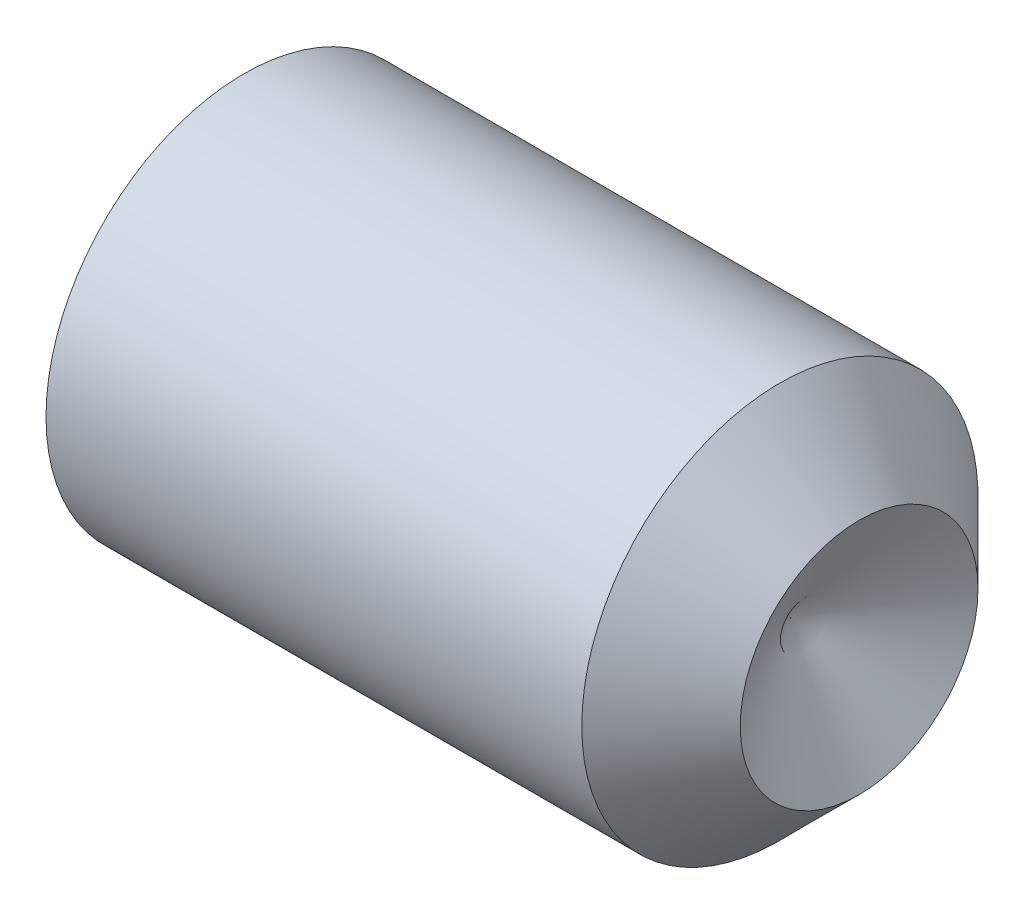
SolidWorks part; units mm, degrees
revolve "BaseBody" add sketch "BodySke" angle 360 about L5
sketch "BodySke" plane through (0, 0, 0) normal (0, 0, 1) x (1, 0, 0)
  line L0 (0, 0) -> (0, 4.172)
  line L1 (0, 4.172) -> (0.478, 5)
  line L2 (0.478, 5) -> (14, 5)
  line L3 (14, 5) -> (16, 3)
  line L4 (14.2679, 0) -> (0, 0)
  line L5 (-12.7, 0) -> (88.9, 0) construction
  line L6 (14.2679, 0) -> (16, 3)
  line L7 (16, 3) -> (16, 12.525) construction
  line L8 (0, -4.172) -> (0.478, -5) construction
  line L9 (14.2679, 0) -> (16, -3) construction
  line L10 (14, -5) -> (16, -3) construction
  line L11 (0.75, 15.875) -> (0.75, -3.175) construction
  dimension "Diameter" = 10
  dimension "Drive_ch_ang" = 60
  dimension "Minor_dia" = 8.344
  dimension "Cup_ang" = 120
  dimension "Cup_dia" = 6
  dimension "Length" = 16
  dimension "Cup_nose_ang" = 45
  dimension "Advance" = 1.5
cosmetic thread "ThreadCosmetic" [suppressed] parameters "Thread_minor"=8.344
ref_plane "Plane1" through (0, 0, 0) normal (0, 0, 1) x (1, 0, 0)
ref_plane "Plane2" through (0, 0, 0) normal (0, 1, 0) x (1, 0, 0)
ref_plane "Plane3" through (0, 0, 0) normal (1, 0, 0) x (0, 0, -1)
sketch "Sketch2" plane through (0, 0, 0) normal (-1, 0, 0) x (0, 0, 1)
  line L0 (1.4434, 2.5) -> (-1.4434, 2.5)
  line L1 (-1.4434, 2.5) -> (-2.8868, 0)
  line L2 (1.4434, 2.5) -> (2.8868, 0)
  line L3 (1.4434, -2.5) -> (2.8868, 0)
  line L4 (1.4434, -2.5) -> (-1.4434, -2.5)
  line L5 (-1.4434, -2.5) -> (-2.8868, 0)
  dimension "Hex_size" = 5
  dimension "D2" = 2.5
  dimension "D3" = 2.5
extrude "Hex" cut sketch "Sketch2" against normal blind 6
sketch "ThdSchSke" plane through (0, 0, 0) normal (0, 0, 1) x (1, 0, 0)
  line L0 (0.478, -4.172) -> (-0.1017, -5)
  line L1 (0.478, -4.172) -> (1.0578, -5)
  line L2 (1.0578, -5) -> (1.0578, -6.25)
  line L3 (-3.175, 0) -> (5.1513, 0) construction
  line L4 (0.478, 5) -> (0.478, -5) construction
  line L5 (1.0578, -6.25) -> (-0.1017, -6.25)
  line L6 (-0.1017, -6.25) -> (-0.1017, -5)
  dimension "Thread_minor" = 8.344
  dimension "Diameter" = 10
revolve "ThreadSchematic" [suppressed] cut sketch "ThdSchSke" angle 360 about L3
pattern_linear "ThdSchPat" [suppressed]
equation "\"D2@Sketch2\" = \"Hex_size@Sketch2\" / 2"
equation "\"D3@Sketch2\" = \"Hex_size@Sketch2\" / 2"
equation "\"Thread_minor@ThreadCosmetic\" = \"Minor_dia@BodySke\""
equation "\"Thread_minor@ThdSchSke\" = \"Thread_minor@ThreadCosmetic\""
equation "\"Diameter@ThdSchSke\" = \"Diameter@BodySke\""
equation "\"Overcut@ThdSchSke\" = \"Diameter@BodySke\" * 1.25"
equation "\"Num_threads@ThdSchPat\" = int( (\"Length@BodySke\" - ( ( ( \"Diameter@BodySke\" - \"Minor_dia@BodySke\" ) * 0.5 ) / tan( \"Drive_ch_ang@BodySke\" * 0.017453292 ) ) - ( ( ( \"Diameter@BodySke\" - \"Cup_dia@BodySke\" ) * 0.5 ) * tan( \"Cup_nose_ang@BodySke\" * 0.017453292 ) ) ) / \"Advance@BodySke\" + 0.999 )  + 1"
equation "\"Advance@ThdSchPat\" = (\"Length@BodySke\" - ( ( ( \"Diameter@BodySke\" - \"Minor_dia@BodySke\" ) * 0.5 ) / tan( \"Drive_ch_ang@BodySke\" * 0.017453292 ) ) - ( ( ( \"Diameter@BodySke\" - \"Cup_dia@BodySke\" ) * 0.5 ) * tan( \"Cup_nose_ang@BodySke\" * 0.017453292 ) ) ) /  (\"Num_threads@ThdSchPat\" - 1) 'relax it"
equation "' \"Num_threads@ThdSchPat\" = \"Num_threads@ThdSchPat\" - sgn( \"Num_threads@ThdSchPat\" - 1) '---chamfered tips only---"
